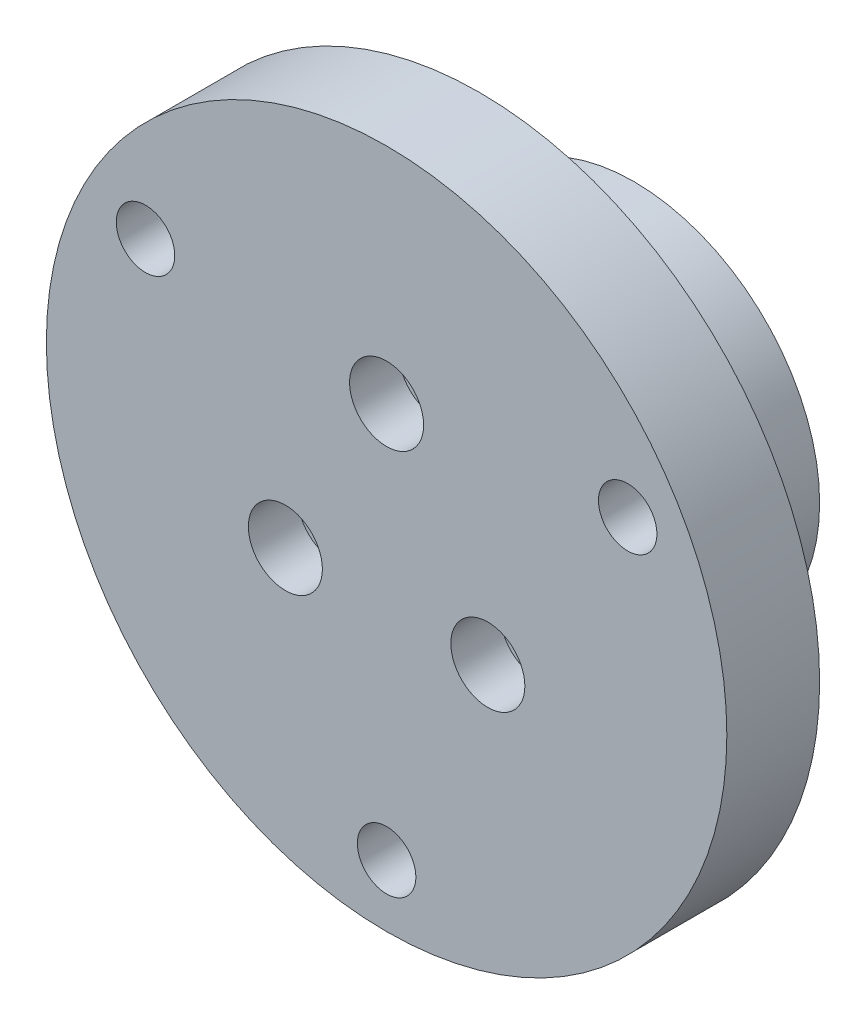
SolidWorks part; units mm, degrees
ref_plane "Front Plane" through (0, 0, 0) normal (0, 0, 1) x (1, 0, 0)
ref_plane "Top Plane" through (0, 0, 0) normal (0, 1, 0) x (1, 0, 0)
ref_plane "Right Plane" through (0, 0, 0) normal (1, 0, 0) x (0, 0, -1)
sketch "Sketch1" plane through (0, 0, 0) normal (0, 0, 1) x (1, 0, 0)
  circle A0 centre (0, 0) radius 9.525
  dimension "D1" = 19.05
extrude "Boss-Extrude1" add sketch "Sketch1" along normal blind 12.7
sketch "Sketch9" plane through (0, 0, 12.7) normal (0, 0, 1) x (1, 0, 0)
  circle A0 centre (0, 0) radius 17.4625
  dimension "D1" = 34.925
extrude "Boss-Extrude2" add sketch "Sketch9" against normal blind 4.7625
sketch "Sketch2" plane through (0, 0, 0) normal (0, 0, -1) x (-1, 0, 0)
  circle A0 centre (0, 0) radius 4.572
  dimension "D1" = 9.144
extrude "Cut-Extrude1" cut sketch "Sketch2" against normal blind 2.9972
hole_wizard "M2 Clearance Hole1" positions "Sketch3" profile "Sketch5" hole size "M2" standard "ANSI Metric" end condition through all
sketch "Sketch3" plane through (0, 0, 0) normal (0, 0, -1) x (-1, 0, 0)
  circle A0 centre (0, 0) radius 6 construction
  point P0 (0, 6)
  dimension "D1" = 12
sketch "Sketch5" plane through (0, 6, 0) normal (1, 0, 0) x (0, 1, 0)
  line L0 (0, 0) -> (0, 12.7)
  line L1 (0, 12.7) -> (1.2, 12.7)
  line L2 (1.2, 12.7) -> (1.2, 0)
  line L5 (1.2, 0) -> (0, 0)
  line L11 (0, -6.35) -> (0, 107.95) construction
  dimension "Thru Hole Dia." = 2.4
  dimension "Thru Hole Depth" = 12.7
sketch "Sketch6" plane through (0, 0, 12.7) normal (0, 0, 1) x (1, 0, 0)
  circle A0 centre (0, 6) radius 1.9
  dimension "D1" = 3.8
extrude "Cut-Extrude2" cut sketch "Sketch6" against normal blind 2.54
sketch "Sketch7" plane through (0, 0, 0) normal (0, 0, -1) x (-1, 0, 0)
  line L0 (0, 6) -> (0, 0) construction
  line L1 (0, 0) -> (12.3733, 7.1438) construction
  circle A0 centre (12.3733, 7.1438) radius 1.5
  circle A1 centre (0, 0) radius 14.2875 construction
  dimension "D1" = 3
  dimension "D3" = 28.575
  dimension "D2" = 60
extrude "Cut-Extrude3" cut sketch "Sketch7" against normal through all
pattern_circular "CirPattern1" count 3 over 360 about axis through (0, 0, 0) along (0, 0, 1) of "Cut-Extrude2", "M2 Clearance Hole1"
pattern_circular "CirPattern2" count 3 over 360 about axis through (0, 0, 0) along (0, 0, 1) of "Cut-Extrude3"
sketch "Sketch10" plane through (0, 0, 7.9375) normal (0, 0, -1) x (-1, 0, 0)
  circle A0 centre (12.3733, 7.1438) radius 2.75
  dimension "D1" = 5.5
fillet "Fillet1" radius 1.5875 1 edges at (9.525, 0, 7.9375)
